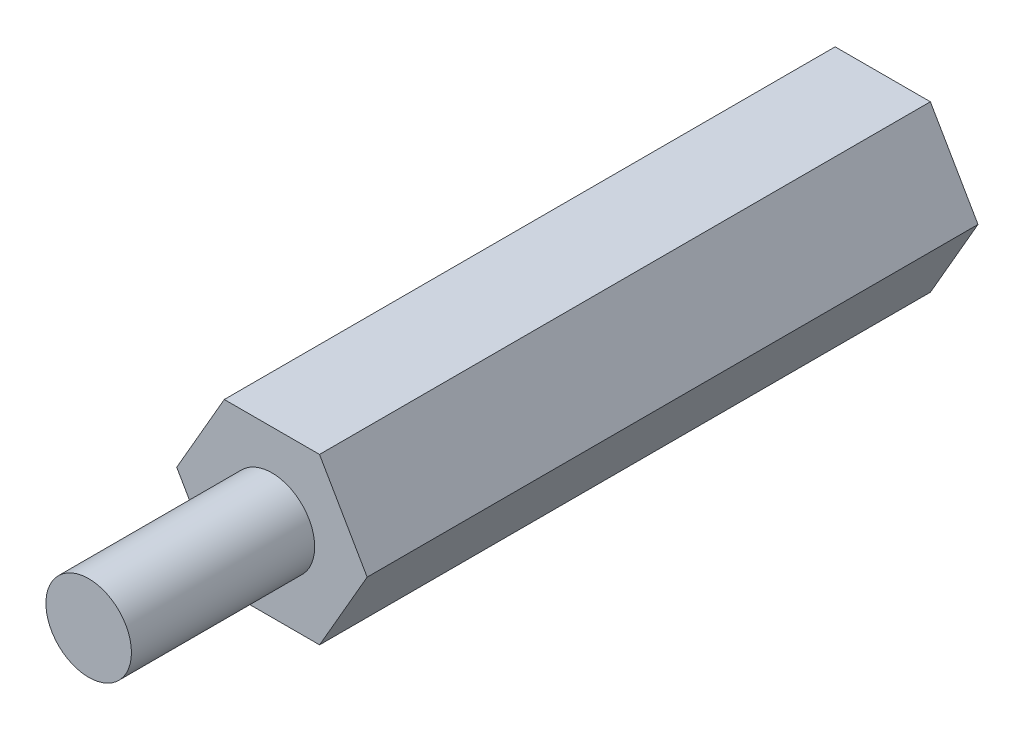
SolidWorks part; units mm, degrees
ref_plane "Plan de face" through (0, 0, 0) normal (0, 0, 1) x (1, 0, 0)
ref_plane "Plan de dessus" through (0, 0, 0) normal (0, 1, 0) x (1, 0, 0)
ref_plane "Plan de droite" through (0, 0, 0) normal (1, 0, 0) x (0, 0, -1)
sketch "Esquisse1" plane through (0, 0, 0) normal (0, 0, 1) x (1, 0, 0)
  line L1 (-1.5597, 2.6995) -> (-3.1177, -0.001)
  line L2 (-3.1177, -0.001) -> (-1.558, -2.7005)
  line L3 (-1.558, -2.7005) -> (1.5597, -2.6995)
  line L4 (1.5597, -2.6995) -> (3.1177, 0.001)
  line L5 (3.1177, 0.001) -> (1.558, 2.7005)
  line L6 (1.558, 2.7005) -> (-1.5597, 2.6995)
  circle A0 centre (0, 0) radius 2.7 construction
  circle A1 centre (0, 0) radius 1.4
  dimension "D2" = 2.8
  dimension "D1" = 5.4
extrude "Boss.-Extru.1" add sketch "Esquisse1" along normal blind 20
sketch "Esquisse2" plane through (0, 0, 20) normal (0, 0, 1) x (1, 0, 0)
  circle A0 centre (0, 0) radius 1.4
  dimension "D1" = 2.8
extrude "Boss.-Extru.2" add sketch "Esquisse2" along normal blind 6 separate body
